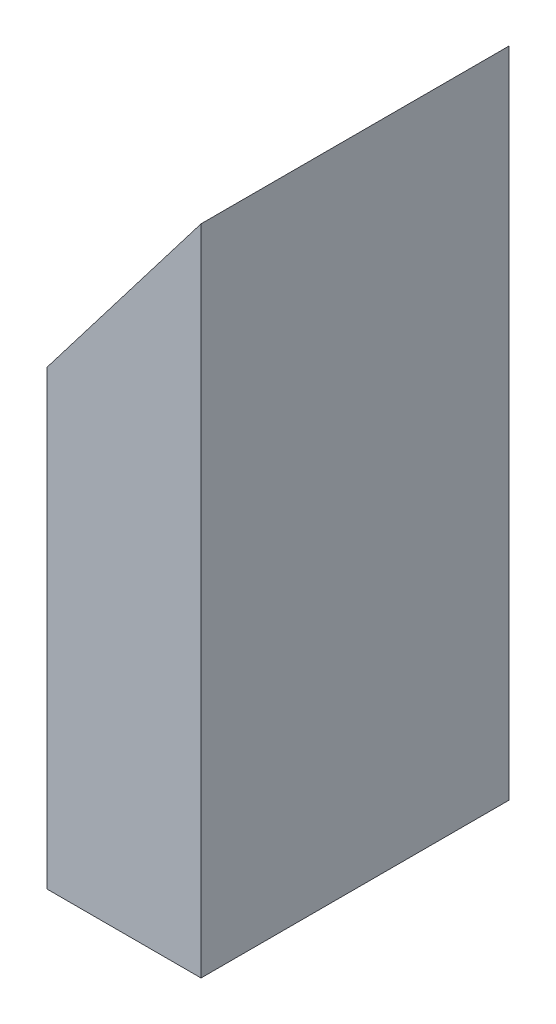
SolidWorks part; units mm, degrees
material "Brass"
ref_plane "Front Plane" through (0, 0, 0) normal (0, 0, 1) x (1, 0, 0)
ref_plane "Top Plane" through (0, 0, 0) normal (0, 1, 0) x (1, 0, 0)
ref_plane "Right Plane" through (0, 0, 0) normal (1, 0, 0) x (0, 0, -1)
sketch "Sketch1" plane through (0, 0, 0) normal (0, 0, 1) x (1, 0, 0)
  line L0 (-1028.7422, -11.9908) -> (48971.2578, -11.9908) construction
  line L1 (-1034.7163, 13.4092) -> (48965.2837, 13.4092) construction
  line L2 (-638.3981, -780.6873) -> (29751.1874, 38924.1372) construction
  line L3 (-30.6064, 13.4092) -> (-32.501, 14.8593) construction
  line L4 (-15.1685, 33.5793) -> (-17.0631, 35.0294) construction
  line L5 (-15.1685, 33.5793) -> (-15.1685, -11.9908) construction
  line L6 (-21.5212, 25.2793) -> (-24.3658, 27.4565) construction
  line L7 (-8.8158, 41.8792) -> (-11.6604, 44.0564) construction
  line L8 (-21.5212, 25.2793) -> (-21.5212, -11.9908) construction
  line L9 (-8.8158, 41.8792) -> (-8.8158, -11.9908) construction
  line L10 (-8.8158, 41.8792) -> (-21.5212, 25.2793)
  line L11 (-21.5212, 25.2793) -> (-21.5212, -11.9908)
  line L12 (-21.5212, -11.9908) -> (-8.8158, -11.9908)
  line L13 (-8.8158, -11.9908) -> (-8.8158, 41.8792)
  line L14 (50.4426, 119.302) -> (36.7374, 129.7918) construction
  line L15 (50.4426, 119.302) -> (50.4426, -11.9908) construction
  line L16 (-8.8158, 41.8792) -> (-21.5212, 41.8792) construction
  line L17 (-21.5212, 41.8792) -> (-21.5212, 25.2793) construction
  line L18 (-21.5212, 41.8792) -> (-13.5093, 35.747) construction
  dimension "D1" = 25.4
  dimension "D2" = 25.4
  dimension "D3" = 20.9042
  dimension "D4" = 10.4521
  dimension "D5" = 37.43
  dimension "D6" = 133.35
  dimension "D7" = 65.6111
  dimension "D8" = 10.0893
  dimension "D9" = 12.7054
  dimension "D10" = 53.87
extrude "Extrude1" add sketch "Sketch1" along normal blind 25.4
hole_wizard "1/4-20 Tapped Hole3" positions "Sketch14" profile "Sketch15" tap size "1/4-20" standard "Ansi Inch"
sketch "Sketch14" plane through (6.9466, -11.9908, 18.0613) normal (0, -1, 0) x (-1, 0, 0)
  point P0 (22.1178, 5.3613)
sketch "Sketch15" plane through (-15.1712, -11.9908, 12.7) normal (1, 0, 0) x (0, 0, -1)
  line L0 (0, 0) -> (0, 18.0438)
  line L1 (0, 18.0438) -> (2.5527, 16.51)
  line L2 (2.5527, 16.51) -> (2.5527, 12.7)
  line L3 (2.5527, 12.7) -> (3.175, 12.7)
  line L4 (3.175, 12.7) -> (3.175, 0)
  line L5 (3.175, 0) -> (0, 0)
  line L10 (0, 18.0438) -> (-2.5527, 16.51) construction
  line L11 (0, -6.35) -> (0, 107.95) construction
  dimension "Tap Drill Dia." = 5.1054
  dimension "Tap Drill Depth" = 16.51
  dimension "Thread Major Dia." = 6.35
  dimension "Drill Angle" = 118
  dimension "Thread Depth Difference" = 3.81
hole_wizard "#10-24 Tapped Hole1" positions "Sketch16" profile "Sketch17" tap size "#10-24" standard "Ansi Inch"
sketch "Sketch16" plane through (13.3224, 70.8034, 18.0613) normal (-0.7941, 0.6078, 0) x (0.6078, 0.7941, 0)
  point P0 (-48.5038, 5.3613)
sketch "Sketch17" plane through (-16.1578, 32.2867, 12.7) normal (0, 0, 1) x (-0.6078, -0.7941, 0)
  line L0 (0, 0) -> (0, 7.4908)
  line L1 (0, 7.4908) -> (1.8986, 6.35)
  line L2 (1.8986, 6.35) -> (1.8986, 3.175)
  line L3 (1.8986, 3.175) -> (2.413, 3.175)
  line L4 (2.413, 3.175) -> (2.413, 0)
  line L5 (2.413, 0) -> (0, 0)
  line L10 (0, 7.4908) -> (-1.8987, 6.35) construction
  line L11 (0, -6.35) -> (0, 107.95) construction
  dimension "Tap Drill Dia." = 3.7973
  dimension "Tap Drill Depth" = 6.35
  dimension "Thread Major Dia." = 4.826
  dimension "Drill Angle" = 118
  dimension "Thread Depth Difference" = 3.175
